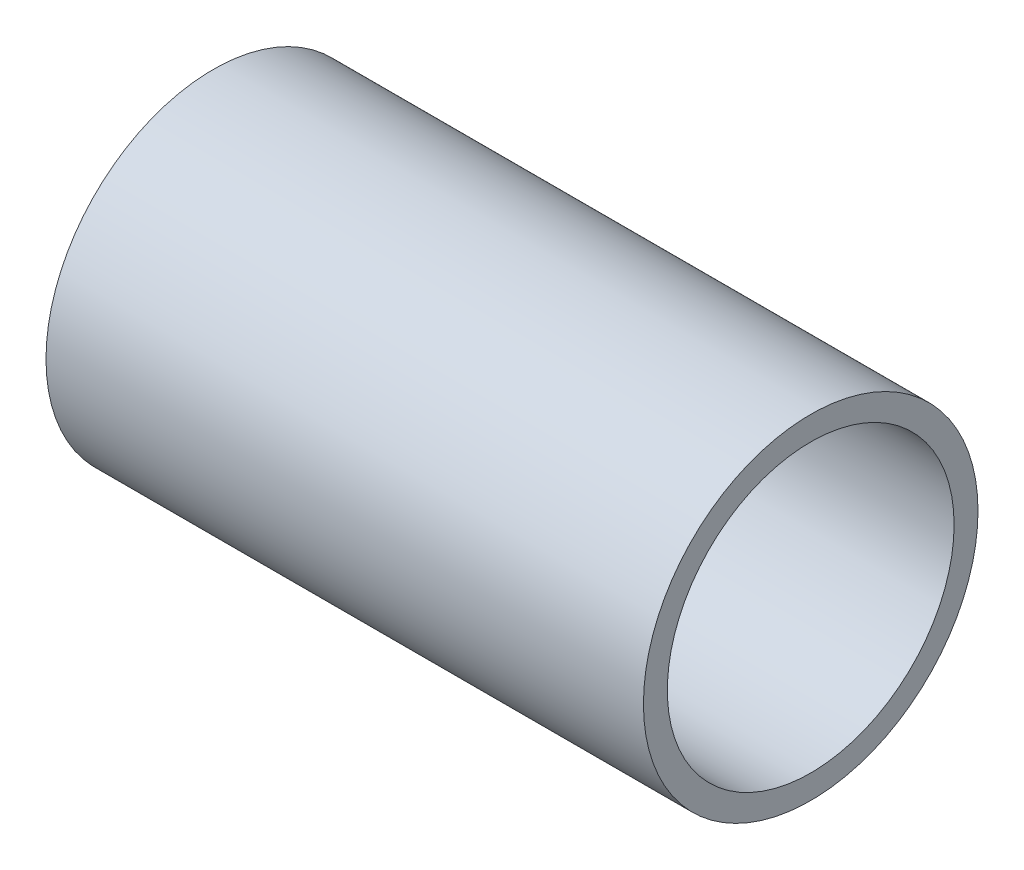
SolidWorks part; units mm, degrees
material "Acrylic (Medium-high impact)"
ref_plane "Front Plane" through (0, 0, 0) normal (0, 0, 1) x (1, 0, 0)
ref_plane "Top Plane" through (0, 0, 0) normal (0, 1, 0) x (1, 0, 0)
ref_plane "Right Plane" through (0, 0, 0) normal (1, 0, 0) x (0, 0, -1)
sketch "Sketch1" plane through (-63.8505, 0, 0) normal (-1, 0, 0) x (0, 0, 1)
  circle A0 centre (19.9949, -1.7637) radius 22.225 construction
  circle A1 centre (19.9949, -1.7637) radius 19.051 construction
  circle A2 centre (19.9949, -1.7637) radius 22.225
  circle A3 centre (19.9949, -1.7637) radius 19.051
extrude "Boss-Extrude1" add sketch "Sketch1" along normal blind 79.375
